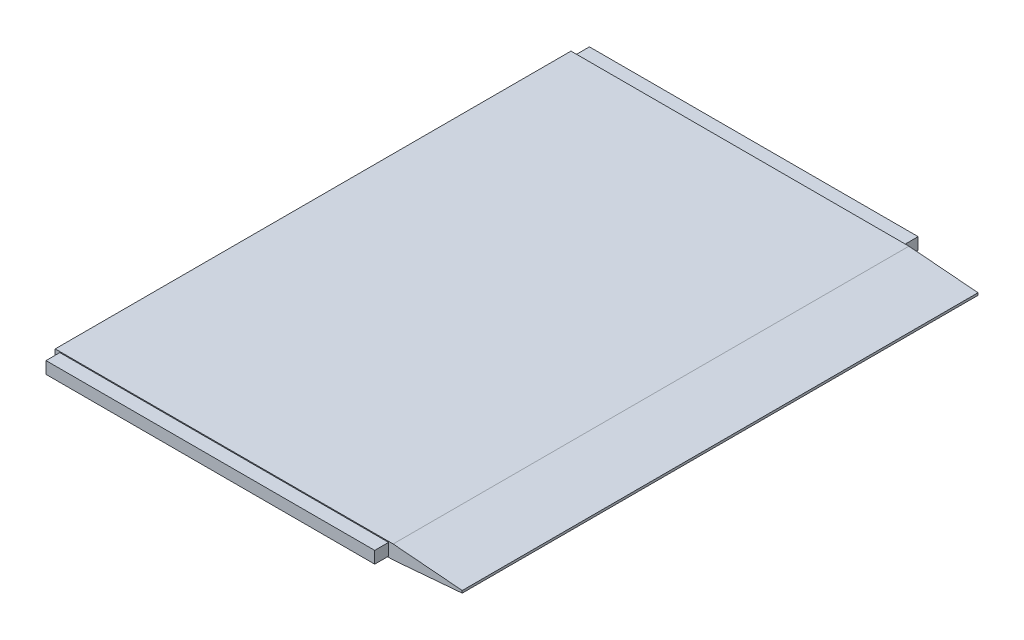
SolidWorks part; units mm, degrees
ref_plane "Front Plane" through (0, 0, 0) normal (0, 0, 1) x (1, 0, 0)
ref_plane "Top Plane" through (0, 0, 0) normal (0, 1, 0) x (1, 0, 0)
ref_plane "Right Plane" through (0, 0, 0) normal (1, 0, 0) x (0, 0, -1)
ref_plane "Plane_z3" through (0, 0, 3) normal (0, 0, 1) x (1, 0, 0)
sketch "Sketch1" plane through (0, 0, 3) normal (0, 0, 1) x (1, 0, 0)
  line L0 (26.5244, -97.9181) -> (99.9067, -97.9181)
  line L1 (99.9067, -97.9181) -> (114.9067, -96.6681)
  line L2 (114.9067, -96.6681) -> (114.9067, -96.1681)
  line L3 (114.9067, -96.1681) -> (99.9067, -94.9181)
  line L4 (99.9067, -94.9181) -> (26.5244, -94.9181)
  line L5 (26.5244, -94.9181) -> (26.5244, -97.9181)
extrude "Body" add sketch "Sketch1" along normal blind 112
sketch "Sketch2" plane through (0, 0, 0) normal (0, 0, 1) x (1, 0, 0)
  line L0 (27.5244, -97.7181) -> (98.9067, -97.7181)
  line L1 (98.9067, -97.7181) -> (98.9067, -95.1181)
  line L2 (98.9067, -95.1181) -> (27.5244, -95.1181)
  line L3 (27.5244, -95.1181) -> (27.5244, -97.7181)
extrude "Tab_low" add sketch "Sketch2" along normal blind 3
ref_plane "Plane_z115" through (0, 0, 115) normal (0, 0, 1) x (1, 0, 0)
sketch "Sketch3" plane through (0, 0, 115) normal (0, 0, 1) x (1, 0, 0)
  line L0 (27.5244, -97.7181) -> (98.9067, -97.7181)
  line L1 (98.9067, -97.7181) -> (98.9067, -95.1181)
  line L2 (98.9067, -95.1181) -> (27.5244, -95.1181)
  line L3 (27.5244, -95.1181) -> (27.5244, -97.7181)
extrude "Tab_high" add sketch "Sketch3" along normal blind 3
